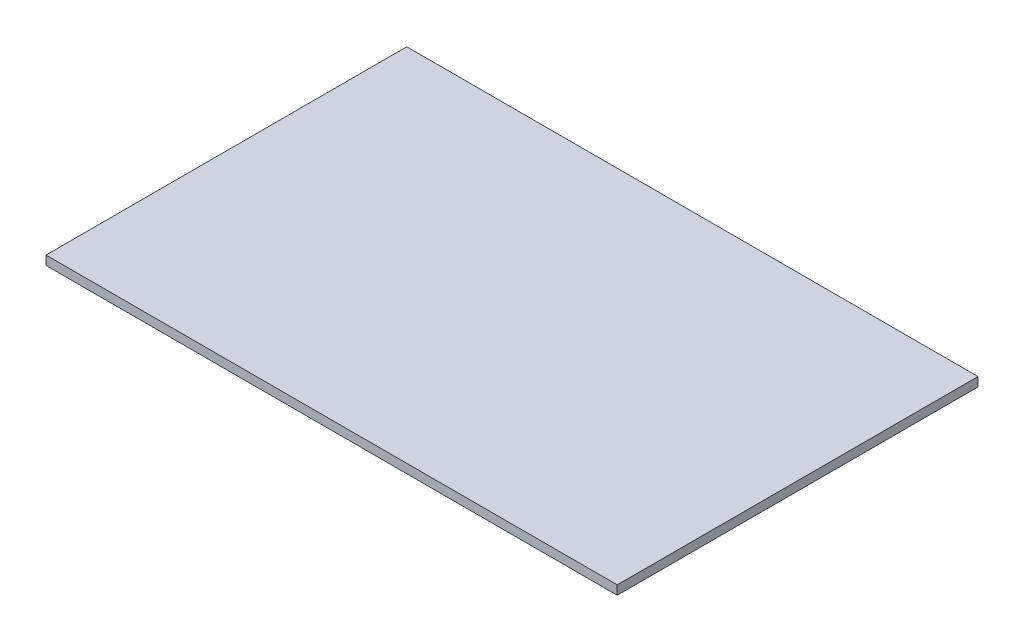
SolidWorks part; units mm, degrees
ref_plane "Front Plane" through (0, 0, 0) normal (0, 0, 1) x (1, 0, 0)
ref_plane "Top Plane" through (0, 0, 0) normal (0, 1, 0) x (1, 0, 0)
ref_plane "Right Plane" through (0, 0, 0) normal (1, 0, 0) x (0, 0, -1)
sketch "Sketch1" plane through (0, 0, 0) normal (0, 1, 0) x (1, 0, 0)
  line L1 (0, -60) -> (190, -60)
  line L2 (0, -60) -> (0, 60)
  line L3 (0, 60) -> (190, 60)
  line L4 (190, -60) -> (190, 60)
  point P7 (0, 0)
  dimension "D1" = 120
  dimension "D2" = 190
extrude "Boss-Extrude1" add sketch "Sketch1" along normal blind 3
